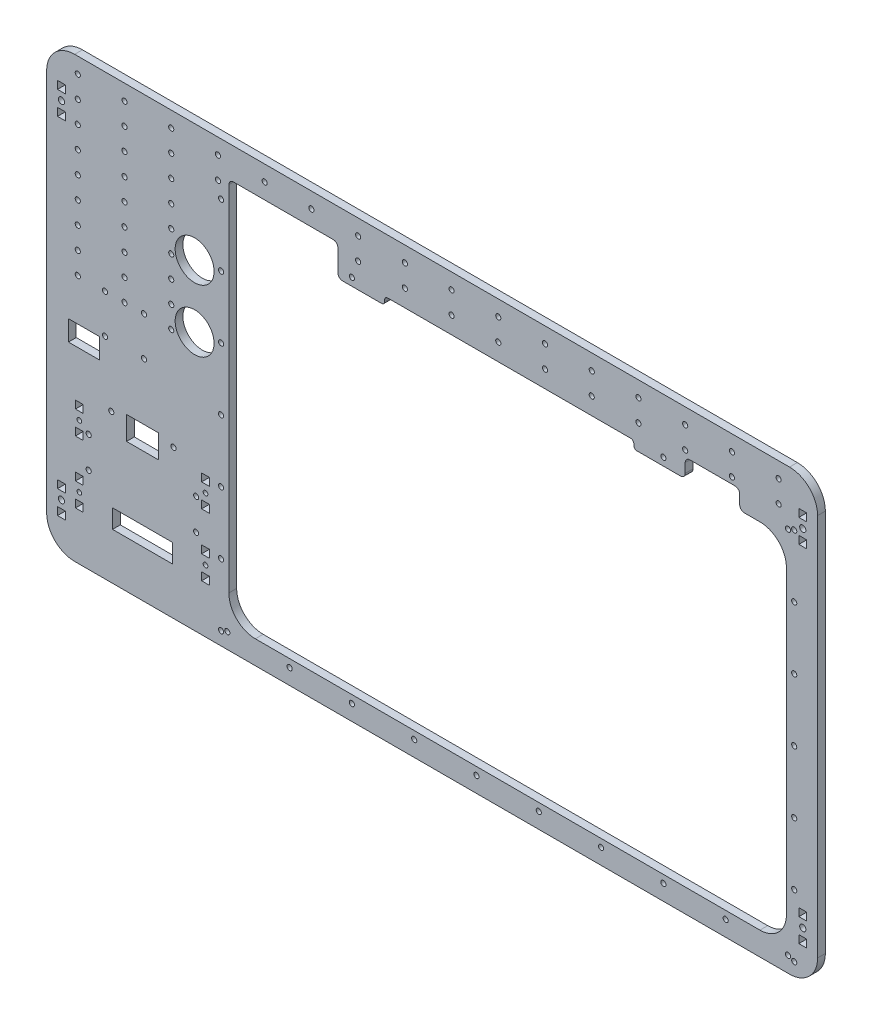
SolidWorks part; units mm, degrees
ref_plane "Plan de face" through (0, 0, 0) normal (0, 0, 1) x (1, 0, 0)
ref_plane "Plan de dessus" through (0, 0, 0) normal (0, 1, 0) x (1, 0, 0)
ref_plane "Plan de droite" through (0, 0, 0) normal (1, 0, 0) x (0, 0, -1)
sketch "Esquisse1" plane through (0, 0, 0) normal (0, 0, 1) x (1, 0, 0)
  line L1 (-495, 282) -> (0, 282)
  line L2 (-495, 282) -> (-495, 0)
  line L3 (-495, 0) -> (0, 0)
  line L4 (0, 282) -> (0, 0)
  line L5 (-378, 242) -> (-20, 242) construction
  line L6 (-378, 242) -> (-378, 15)
  line L7 (-378, 15) -> (-20, 15)
  line L8 (-20, 242) -> (-20, 15)
  line L16 (-378, 242) -> (-378, 262)
  line L17 (-378, 262) -> (-308, 262)
  line L18 (-308, 262) -> (-308, 242)
  line L20 (-457.5, 135) -> (-432.5, 135) construction
  line L21 (-432.5, 135) -> (-432.5, 160) construction
  line L22 (-432.5, 160) -> (-457.5, 160) construction
  line L23 (-457.5, 160) -> (-457.5, 135) construction
  line L26 (-20, 128.5) -> (-378, 128.5) construction
  line L27 (-495, 272) -> (0, 272) construction
  line L31 (0, 258) -> (-495, 258) construction
  line L42 (-475, 272) -> (-475, 258) construction
  line L43 (-15, 242) -> (-15, 10) construction
  line L44 (-15, 10) -> (-383, 10) construction
  line L45 (-383, 10) -> (-383, 242) construction
  line L46 (-199, 15) -> (-199, 242) construction
  line L47 (-179, 247) -> (-179, 282) construction
  line L48 (-118, 242) -> (-85, 242)
  line L49 (-85, 242) -> (-85, 254)
  line L50 (-247.5, 0) -> (-247.5, 282) construction
  line L51 (0, 141) -> (-495, 141) construction
  line L52 (-400, 282) -> (-400, 0) construction
  line L53 (-308, 242) -> (-278, 242)
  line L54 (-278, 242) -> (-278, 247)
  line L55 (-278, 247) -> (-118, 247)
  line L56 (-118, 247) -> (-118, 242)
  line L57 (-118, 242) -> (-20, 242) construction
  line L58 (-85, 254) -> (-50, 254)
  line L59 (-50, 254) -> (-50, 242)
  line L60 (-50, 242) -> (-20, 242)
  circle A6 centre (-457.5, 160) radius 1.65
  circle A7 centre (-432.5, 160) radius 1.65
  circle A8 centre (-432.5, 135) radius 1.65
  circle A9 centre (-457.5, 135) radius 1.65
  circle A10 centre (-475, 272) radius 1.65
  circle A11 centre (-475, 258) radius 1.65
  circle A12 centre (-445, 258) radius 1.65
  circle A13 centre (-445, 272) radius 1.65
  circle A54 centre (-379, 10) radius 1.65
  circle A55 centre (-339, 10) radius 1.65
  circle A56 centre (-299, 10) radius 1.65
  circle A57 centre (-259, 10) radius 1.65
  circle A58 centre (-219, 10) radius 1.65
  circle A59 centre (-179, 10) radius 1.65
  circle A60 centre (-139, 10) radius 1.65
  circle A61 centre (-99, 10) radius 1.65
  circle A62 centre (-59, 10) radius 1.65
  circle A63 centre (-19, 10) radius 1.65
  circle A66 centre (-299, 247) radius 1.65
  circle A67 centre (-259, 247) radius 1.65 construction
  circle A68 centre (-219, 247) radius 1.65 construction
  circle A69 centre (-179, 247) radius 1.65 construction
  circle A70 centre (-139, 247) radius 1.65 construction
  circle A71 centre (-99, 247) radius 1.65
  circle A72 centre (-59, 247) radius 1.65 construction
  circle A73 centre (-19, 247) radius 1.65
  circle A114 centre (-15, 248.5) radius 1.65
  circle A115 centre (-15, 208.5) radius 1.65
  circle A116 centre (-15, 168.5) radius 1.65
  circle A117 centre (-15, 128.5) radius 1.65
  circle A118 centre (-15, 88.5) radius 1.65
  circle A119 centre (-15, 48.5) radius 1.65
  circle A120 centre (-15, 8.5) radius 1.65
  circle A121 centre (-383, 8.5) radius 1.65
  circle A122 centre (-383, 48.5) radius 1.65
  circle A123 centre (-383, 88.5) radius 1.65
  circle A124 centre (-383, 128.5) radius 1.65
  circle A125 centre (-383, 168.5) radius 1.65
  circle A126 centre (-383, 208.5) radius 1.65
  circle A127 centre (-383, 248.5) radius 1.65
  circle A128 centre (-400, 166) radius 12.5
  circle A129 centre (-400, 206) radius 12.5
  circle A130 centre (-415, 258) radius 1.65
  circle A131 centre (-415, 272) radius 1.65
  circle A132 centre (-445, 244) radius 1.65 [skipped]
  circle A133 centre (-475, 244) radius 1.65 construction
  circle A134 centre (-415, 244) radius 1.65
  circle A135 centre (-445, 244) radius 1.65
  circle A136 centre (-475, 244) radius 1.65
  circle A137 centre (-415, 230) radius 1.65
  circle A138 centre (-445, 230) radius 1.65
  circle A139 centre (-475, 230) radius 1.65
  circle A140 centre (-415, 216) radius 1.65
  circle A141 centre (-445, 216) radius 1.65
  circle A142 centre (-475, 216) radius 1.65
  circle A143 centre (-415, 202) radius 1.65
  circle A144 centre (-445, 202) radius 1.65
  circle A145 centre (-475, 202) radius 1.65
  circle A146 centre (-415, 188) radius 1.65
  circle A147 centre (-445, 188) radius 1.65
  circle A148 centre (-475, 188) radius 1.65
  circle A149 centre (-415, 174) radius 1.65
  circle A150 centre (-445, 174) radius 1.65
  circle A151 centre (-475, 174) radius 1.65
  circle A152 centre (-415, 160) radius 1.65
  circle A153 centre (-445, 160) radius 1.65
  circle A154 centre (-475, 160) radius 1.65
  circle A161 centre (-385, 272) radius 1.65
  circle A162 centre (-385, 258) radius 1.65
  circle A163 centre (-355, 272) radius 1.65
  circle A164 centre (-355, 258) radius 1.65 construction
  circle A165 centre (-325, 272) radius 1.65
  circle A166 centre (-325, 258) radius 1.65 construction
  circle A167 centre (-295, 272) radius 1.65
  circle A168 centre (-295, 258) radius 1.65
  circle A169 centre (-265, 272) radius 1.65
  circle A170 centre (-265, 258) radius 1.65
  circle A171 centre (-235, 272) radius 1.65
  circle A172 centre (-235, 258) radius 1.65
  circle A173 centre (-205, 272) radius 1.65
  circle A174 centre (-205, 258) radius 1.65
  circle A175 centre (-175, 272) radius 1.65
  circle A176 centre (-175, 258) radius 1.65
  circle A177 centre (-145, 272) radius 1.65
  circle A178 centre (-145, 258) radius 1.65
  circle A179 centre (-115, 272) radius 1.65
  circle A180 centre (-115, 258) radius 1.65
  circle A181 centre (-85, 272) radius 1.65
  circle A182 centre (-85, 258) radius 1.65
  circle A183 centre (-55, 272) radius 1.65
  circle A184 centre (-55, 258) radius 1.65
  circle A185 centre (-25, 272) radius 1.65
  circle A186 centre (-25, 258) radius 1.65
  point P23 (-457.5, 162.8847)
  point P40 (-483, 259.5)
  point P89 (-458.2201, 153.5)
  point P90 (0, 0)
  point P91 (-458.2201, 153.5)
  point P92 (-432.5, 128.5)
  point P93 (-519.1971, 141)
  line B0 (-485.5, 35) -> (-485.5, 25) construction
  line B1 (-483, 35) -> (-483, 40)
  line B2 (-483, 35) -> (-488, 35)
  line B3 (-488, 35) -> (-488, 40)
  line B4 (-483, 40) -> (-488, 40)
  line B5 (-483, 25) -> (-483, 20)
  line B6 (-483, 25) -> (-488, 25)
  line B7 (-488, 25) -> (-488, 20)
  line B8 (-483, 20) -> (-488, 20)
  line B9 (-485.5, 30) -> (-478.5276, 30) construction
  circle B10 centre (-485.5, 30) radius 2
  line B11 (-485.5, 247) -> (-485.5, 257) construction
  line B12 (-483, 247) -> (-483, 242)
  line B13 (-483, 247) -> (-488, 247)
  line B14 (-488, 247) -> (-488, 242)
  line B15 (-483, 242) -> (-488, 242)
  line B16 (-483, 257) -> (-483, 262)
  line B17 (-483, 257) -> (-488, 257)
  line B18 (-488, 257) -> (-488, 262)
  line B19 (-483, 262) -> (-488, 262)
  line B20 (-485.5, 252) -> (-478.5276, 252) construction
  circle B21 centre (-485.5, 252) radius 2
  line B22 (-9.5, 35) -> (-9.5, 25) construction
  line B23 (-12, 35) -> (-12, 40)
  line B24 (-12, 35) -> (-7, 35)
  line B25 (-7, 35) -> (-7, 40)
  line B26 (-12, 40) -> (-7, 40)
  line B27 (-12, 25) -> (-12, 20)
  line B28 (-12, 25) -> (-7, 25)
  line B29 (-7, 25) -> (-7, 20)
  line B30 (-12, 20) -> (-7, 20)
  line B31 (-9.5, 30) -> (-16.4724, 30) construction
  circle B32 centre (-9.5, 30) radius 2
  line B33 (-9.5, 247) -> (-9.5, 257) construction
  line B34 (-12, 247) -> (-12, 242)
  line B35 (-12, 247) -> (-7, 247)
  line B36 (-7, 247) -> (-7, 242)
  line B37 (-12, 242) -> (-7, 242)
  line B38 (-12, 257) -> (-12, 262)
  line B39 (-12, 257) -> (-7, 257)
  line B40 (-7, 257) -> (-7, 262)
  line B41 (-12, 262) -> (-7, 262)
  line B42 (-9.5, 252) -> (-16.4724, 252) construction
  circle B43 centre (-9.5, 252) radius 2
  line B44 (-423.3, 83.4) -> (-443.7, 83.4)
  line B45 (-423.3, 83.4) -> (-423.3, 98.4)
  line B46 (-423.3, 98.4) -> (-443.7, 98.4)
  line B47 (-443.7, 83.4) -> (-443.7, 98.4)
  line B48 (-414.3, 30) -> (-452.7, 30)
  line B49 (-414.3, 30) -> (-414.3, 42)
  line B50 (-414.3, 42) -> (-452.7, 42)
  line B51 (-452.7, 30) -> (-452.7, 42)
  line B52 (-395.5, 25) -> (-471.5, 25) construction
  line B53 (-395.5, 25) -> (-395.5, 110.2) construction
  line B54 (-395.5, 110.2) -> (-471.5, 110.2) construction
  line B55 (-471.5, 25) -> (-471.5, 110.2) construction
  line B56 (-388, 25) -> (-388, 110.2) construction
  line B57 (-388, 110.2) -> (-479, 110.2) construction
  line B58 (-479, 110.2) -> (-479, 25) construction
  line B59 (-395.5, 26.0095) -> (-395.5, 110.2) construction
  line B60 (-471.5, 25) -> (-471.5, 110.2) construction
  line B61 (-479, 25) -> (-388, 25) construction
  line B62 (-388, 25) -> (-388, 110.2) construction
  line B63 (-479, 110.2) -> (-479, 25) construction
  line B64 (-388, 110.2) -> (-388, 118.2) construction
  line B65 (-388, 118.2) -> (-479, 118.2) construction
  line B66 (-479, 118.2) -> (-479, 110.2) construction
  line B67 (-433.5, 25) -> (-433.5, 118.2) construction
  line B68 (-388, 25) -> (-388, 60) construction
  line B69 (-388, 60) -> (-383, 60) construction
  line B70 (-383, 60) -> (-383, 65) construction
  line B71 (-383, 65) -> (-388, 65) construction
  line B72 (-388, 65) -> (-388, 110.2) construction
  line B73 (-479, 25) -> (-479, 60) construction
  line B74 (-479, 60) -> (-484, 60) construction
  line B75 (-484, 60) -> (-484, 65) construction
  line B76 (-484, 65) -> (-479, 65) construction
  line B77 (-479, 65) -> (-479, 110.2) construction
  circle B78 centre (-399, 55.2) radius 1.65
  circle B79 centre (-399, 75.2) radius 1.65
  circle B80 centre (-413.5, 95.2) radius 1.65
  circle B81 centre (-453.5, 95.2) radius 1.65
  circle B82 centre (-468, 75.2) radius 1.65
  circle B83 centre (-468, 55.2) radius 1.65
  line B84 (-474, 35) -> (-474, 45) construction
  line B85 (-476.5, 35) -> (-476.5, 30)
  line B86 (-476.5, 35) -> (-471.5, 35)
  line B87 (-471.5, 35) -> (-471.5, 30)
  line B88 (-476.5, 30) -> (-471.5, 30)
  line B89 (-476.5, 45) -> (-476.5, 50)
  line B90 (-476.5, 45) -> (-471.5, 45)
  line B91 (-471.5, 45) -> (-471.5, 50)
  line B92 (-476.5, 50) -> (-471.5, 50)
  line B93 (-474, 40) -> (-480.9724, 40) construction
  circle B94 centre (-474, 40) radius 1.5
  line B95 (-474, 75) -> (-474, 85) construction
  line B96 (-476.5, 75) -> (-476.5, 70)
  line B97 (-476.5, 75) -> (-471.5, 75)
  line B98 (-471.5, 75) -> (-471.5, 70)
  line B99 (-476.5, 70) -> (-471.5, 70)
  line B100 (-476.5, 85) -> (-476.5, 90)
  line B101 (-476.5, 85) -> (-471.5, 85)
  line B102 (-471.5, 85) -> (-471.5, 90)
  line B103 (-476.5, 90) -> (-471.5, 90)
  line B104 (-474, 80) -> (-480.9724, 80) construction
  circle B105 centre (-474, 80) radius 1.5
  line B106 (-393, 45) -> (-393, 35) construction
  line B107 (-390.5, 45) -> (-390.5, 50)
  line B108 (-390.5, 45) -> (-395.5, 45)
  line B109 (-395.5, 45) -> (-395.5, 50)
  line B110 (-390.5, 50) -> (-395.5, 50)
  line B111 (-390.5, 35) -> (-390.5, 30)
  line B112 (-390.5, 35) -> (-395.5, 35)
  line B113 (-395.5, 35) -> (-395.5, 30)
  line B114 (-390.5, 30) -> (-395.5, 30)
  line B115 (-393, 40) -> (-386.0276, 40) construction
  circle B116 centre (-393, 40) radius 1.5
  line B117 (-393, 85) -> (-393, 75) construction
  line B118 (-390.5, 85) -> (-390.5, 90)
  line B119 (-390.5, 85) -> (-395.5, 85)
  line B120 (-395.5, 85) -> (-395.5, 90)
  line B121 (-390.5, 90) -> (-395.5, 90)
  line B122 (-390.5, 75) -> (-390.5, 70)
  line B123 (-390.5, 75) -> (-395.5, 75)
  line B124 (-395.5, 75) -> (-395.5, 70)
  line B125 (-390.5, 70) -> (-395.5, 70)
  line B126 (-393, 80) -> (-386.0276, 80) construction
  circle B127 centre (-393, 80) radius 1.5
  line B128 (-461.2, 120) -> (-481, 120)
  line B129 (-461.2, 120) -> (-461.2, 133)
  line B130 (-461.2, 133) -> (-481, 133)
  line B131 (-481, 120) -> (-481, 133)
  dimension "D4" = 20
  dimension "D5" = 10
  dimension "D8" = 7
  dimension "D17" = 25
  dimension "D21" = 3.3
  dimension "D1" = 227
  dimension "D2" = 358
  dimension "D3" = 70
  dimension "D6" = 25
  dimension "D7" = 25
  dimension "D9" = 3
  dimension "D10" = 22
  dimension "D11" = 6
  dimension "D12" = 15
  dimension "D13" = 20
  dimension "D14" = 2
  dimension "D15" = 30
  dimension "D16" = 20
  dimension "D18" = 5
  dimension "D19" = 5
  dimension "D20" = 5
  dimension "D22" = 20
  dimension "D23" = 40
  dimension "D25" = 14
  dimension "D26" = 7
  dimension "D27" = 40
  dimension "D28" = 8
  dimension "D29" = 20
  dimension "D31" = 40
  dimension "D32" = 10
  dimension "D33" = 100
  dimension "D34" = 495
  dimension "D30" = 8
  dimension "D35" = 260
  dimension "D36" = 5
  dimension "D37" = 10
  dimension "D38" = 14
  dimension "D39" = 14
  dimension "D40" = 37.5
  dimension "D41" = 30
  dimension "D42" = 30
  dimension "D43" = 35
  dimension "D44" = 12
  dimension "D45" = 2
  dimension "D46" = 8
  dimension "D24" = 10
sketch_block_instance "Trou M4 plots 5mm-1"
sketch_block "Bloc2" parameters "D2"=4, "D1"=5, "D3"=5, "D4"=10
sketch_block_instance "Bloc2-2"
sketch_block_instance "Bloc2-3"
sketch_block_instance "Bloc2-4"
sketch_block_instance "Bloc1-4"
sketch_block "Bloc1" parameters "D2"=3.3, "D1"=15, "D3"=35, "D4"=8, "D5"=91, "D6"=7.5, "D7"=5, "D8"=5, "D9"=35, "D10"=38.4, "D11"=93.2, "D12"=76, "D13"=12
sketch_block_instance "Trou M3 plots 5mm-1"
sketch_block "Trou M3 plots 5mm" parameters "D2"=3, "D1"=5, "D3"=5, "D4"=10
sketch_block_instance "Trou M3 plots 5mm-2"
sketch_block_instance "Trou M3 plots 5mm-3"
sketch_block_instance "Trou M3 plots 5mm-4"
sketch_block_instance "Insert_Interrupteur_RS_419-744-3"
sketch_block "Insert_Interrupteur_RS_419-744" parameters "D1"=19.8, "D2"=13
extrude "Boss.-Extru.1" add sketch "Esquisse1" along normal blind 5
fillet "Congé1" radius 18 4 edges at (-495, 0, 2.5) (0, 0, 2.5) (0, 282, 2.5) (-495, 282, 2.5)
fillet "Congé2" radius 17 3 edges at (-378, 15, 2.5) (-20, 15, 2.5) (-20, 242, 2.5)
fillet "Congé3" radius 3 7 edges at (-378, 262, 2.5) (-308, 262, 2.5) (-308, 242, 2.5) (-85, 242, 2.5) (-50, 242, 2.5) (-50, 254, 2.5) (-85, 254, 2.5)
fillet "Congé4" radius 2 4 edges at (-118, 247, 2.5) (-278, 247, 2.5) (-278, 242, 2.5) (-118, 242, 2.5)
